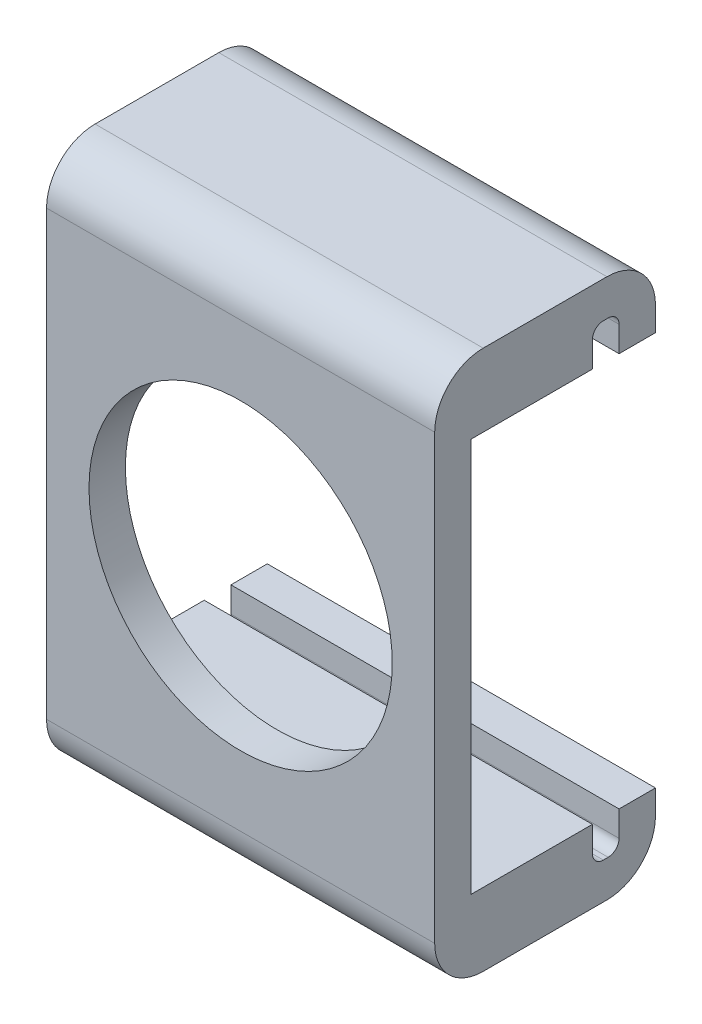
SolidWorks part; units mm, degrees
ref_plane "Vorne" through (0, 0, 0) normal (0, 0, 1) x (1, 0, 0)
ref_plane "Oben" through (0, 0, 0) normal (0, 1, 0) x (1, 0, 0)
ref_plane "Rechts" through (0, 0, 0) normal (1, 0, 0) x (0, 0, -1)
sketch "Skizze1" plane through (0, 0, 0) normal (0, 0, 1) x (1, 0, 0)
  line L1 (0, 0) -> (32, 0)
  line L2 (0, 0) -> (0, 44.5)
  line L3 (0, 44.5) -> (32, 44.5)
  line L4 (32, 0) -> (32, 44.5)
  dimension "D1" = 44.5
  dimension "D2" = 32
extrude "Aufsatz-Linear austragen1" add sketch "Skizze1" along normal blind 3
sketch "Skizze2" plane through (32, 0, 0) normal (1, 0, 0) x (0, 0, -1)
  line L0 (0, 44.5) -> (15.2, 44.5)
  line L1 (15.2, 44.5) -> (15.2, 38.5)
  line L2 (15.2, 38.5) -> (12.2, 38.5)
  line L3 (12.2, 38.5) -> (12.2, 40.6)
  line L4 (11.3, 41.5) -> (10.9, 41.5)
  line L6 (-3, 38.5) -> (10, 38.5)
  line L7 (-3, 0) -> (-3, 44.5) construction
  line L8 (10, 38.5) -> (10, 40.6)
  line L9 (0, 44.5) -> (-3, 44.5)
  line L10 (-3, 44.5) -> (-3, 38.5)
  line L11 (0, 22.25) -> (27.0703, 22.25) construction
  line L12 (0, 0) -> (0, 44.5) construction
  line L13 (0, 0) -> (-3, 0)
  line L14 (0, 0) -> (15.2, 0)
  line L15 (15.2, 0) -> (15.2, 6)
  line L16 (15.2, 6) -> (12.2, 6)
  line L17 (12.2, 6) -> (12.2, 3.9)
  line L18 (11.3, 3) -> (10.9, 3)
  line L19 (10, 6) -> (10, 3.9)
  line L20 (-3, 6) -> (10, 6)
  line L21 (-3, 0) -> (-3, 6)
  arc A0 (12.2, 40.6) -> (11.3, 41.5) centre (11.3, 40.6) ccw
  arc A1 (10, 40.6) -> (10.9, 41.5) centre (10.9, 40.6) cw
  arc A2 (12.2, 3.9) -> (11.3, 3) centre (11.3, 3.9) cw
  arc A3 (10, 3.9) -> (10.9, 3) centre (10.9, 3.9) ccw
  point P13 (12.2, 41.5)
  point P18 (10, 41.5)
  dimension "D6" = 0.9
  dimension "D1" = 2.2
  dimension "D2" = 6
  dimension "D3" = 3
  dimension "D4" = 3
  dimension "D5" = 13
extrude "Aufsatz-Linear austragen2" add sketch "Skizze2" against normal through all
sketch "Skizze3" plane through (0, 0, 0) normal (0, 0, -1) x (-1, 0, 0)
  circle A0 centre (-16, 22.25) radius 12.5
  dimension "D1" = 25
extrude "Schnitt-Linear austragen1" cut sketch "Skizze3" against normal through all
fillet "Verrundung1" radius 4 2 edges at (16, 0, 3) (16, 44.5, 3)
fillet "Verrundung2" radius 4 2 edges at (16, 0, -15.2) (16, 44.5, -15.2)
